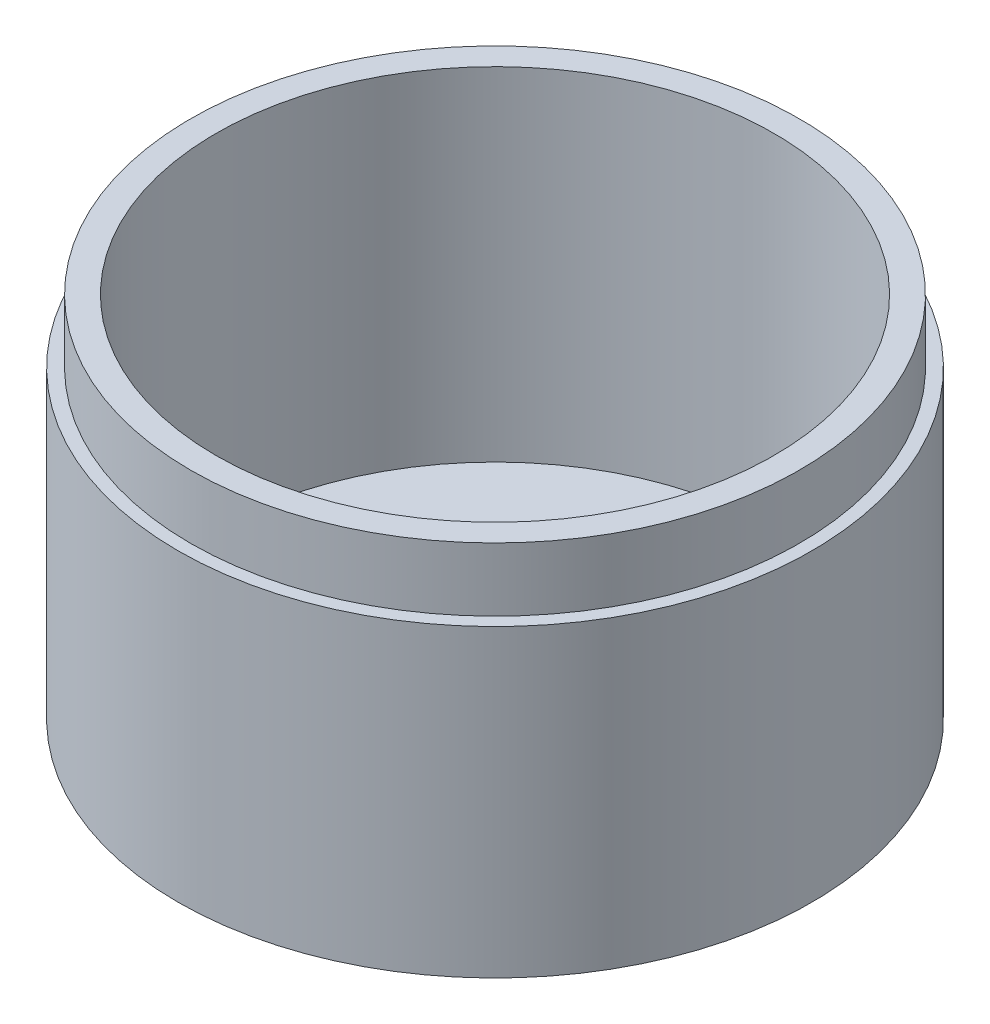
SolidWorks part; units mm, degrees
ref_plane "Front Plane" through (0, 0, 0) normal (0, 0, 1) x (1, 0, 0)
ref_plane "Top Plane" through (0, 0, 0) normal (0, 1, 0) x (1, 0, 0)
ref_plane "Right Plane" through (0, 0, 0) normal (1, 0, 0) x (0, 0, -1)
sketch "Sketch1" plane through (0, 0, 0) normal (0, 1, 0) x (1, 0, 0)
  circle A0 centre (0, 0) radius 25
  dimension "D1" = 50
extrude "Boss-Extrude1" add sketch "Sketch1" along normal blind 29
sketch "Sketch2" plane through (0, 29, 0) normal (0, 1, 0) x (1, 0, 0)
  circle A0 centre (0, 0) radius 24
  circle A1 centre (0, 0) radius 25 construction
  circle A2 centre (0, 0) radius 25
  dimension "D1" = 1
extrude "Cut-Extrude1" cut sketch "Sketch2" against normal blind 5
sketch "Sketch3" plane through (0, 29, 0) normal (0, 1, 0) x (1, 0, 0)
  circle A0 centre (0, 0) radius 22
  circle A1 centre (0, 0) radius 24 construction
  dimension "D1" = 2
extrude "Cut-Extrude2" cut sketch "Sketch3" against normal offset from surface (27 mm away) 2 up to face at (0, 0, 25)
